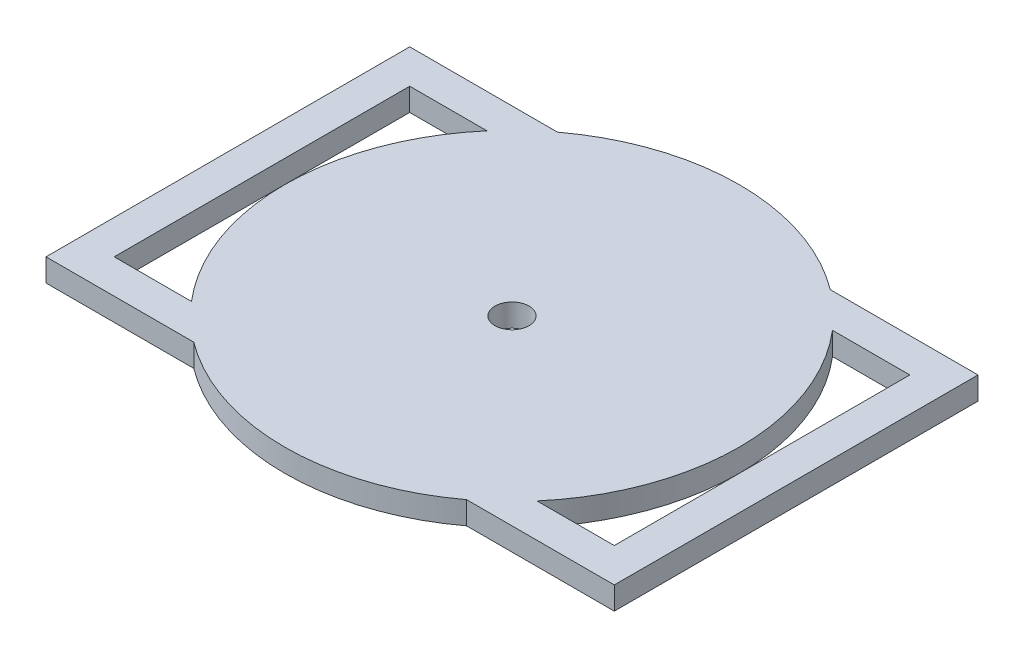
SolidWorks part; units mm, degrees
ref_plane "Front Plane" through (0, 0, 0) normal (0, 0, 1) x (1, 0, 0)
ref_plane "Top Plane" through (0, 0, 0) normal (0, 1, 0) x (1, 0, 0)
ref_plane "Right Plane" through (0, 0, 0) normal (1, 0, 0) x (0, 0, -1)
sketch "Sketch1" plane through (0, 0, 0) normal (0, 1, 0) x (1, 0, 0)
  line L0 (0, -55) -> (0, 55) construction
  line L1 (-15.1987, 13) -> (-22, 13)
  line L3 (-15.1987, -13) -> (-22, -13)
  line L4 (-22, 13) -> (-22, -13)
  line L5 (-12, 16) -> (-25, 16)
  line L7 (-12, -16) -> (-25, -16)
  line L8 (-25, 16) -> (-25, -16)
  line L9 (25, 16) -> (25, -16)
  line L10 (12, -16) -> (25, -16)
  line L11 (12, 16) -> (25, 16)
  line L12 (22, 13) -> (22, -13)
  line L13 (15.1987, -13) -> (22, -13)
  line L14 (15.1987, 13) -> (22, 13)
  circle A0 centre (0, 0) radius 20
  circle A1 centre (0, 0) radius 1.5
  point P11 (-22, 0)
  dimension "D1" = 40
  dimension "D7" = 3
  dimension "D2" = 26
  dimension "D3" = 3
  dimension "D4" = 3
  dimension "D5" = 3
  dimension "D6" = 22
extrude "Boss-Extrude1" add sketch "Sketch1" along normal blind 2 contours A0 | A0 L5 L8 L7 L3 L4 L1 | A0 L10 L9 L11 L14 L12 L13
